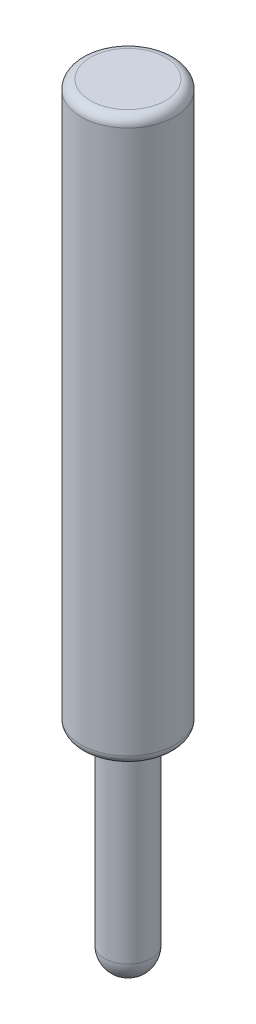
SolidWorks part; units mm, degrees
ref_plane "Front Plane" through (0, 0, 0) normal (0, 0, 1) x (1, 0, 0)
ref_plane "Top Plane" through (0, 0, 0) normal (0, 1, 0) x (1, 0, 0)
ref_plane "Right Plane" through (0, 0, 0) normal (1, 0, 0) x (0, 0, -1)
sketch "草图1" plane through (0, 0, 0) normal (0, 1, 0) x (1, 0, 0)
  circle A0 centre (0, 0) radius 5
  dimension "D1" = 10
extrude "凸台-拉伸1" add sketch "草图1" along normal blind 60
sketch "草图2" plane through (0, 0, 0) normal (0, 1, 0) x (1, 0, 0)
  circle A0 centre (0, 0) radius 2.5
  dimension "D1" = 5
extrude "凸台-拉伸2" add sketch "草图2" against normal blind 20
sketch "草图3" plane through (0, 0, 0) normal (0, 0, 1) x (1, 0, 0)
  line L0 (-2.5, -20) -> (2.5, -20) construction
  line L1 (0, -17.5) -> (0, -22.5)
  circle A0 centre (0, -20) radius 2.5
revolve "旋转1" add sketch "草图3" angle 360 about L1
fillet "圆角1" radius 1 2 edges at (0, 60, 5) (0, 0, 5)
sketch "草图4" plane through (0, 0, 0) normal (0, 0, 1) x (1, 0, 0)
  arc A0 (-2.5, -20) -> (2.5, -20) centre (0, -20) ccw construction
  point P0 (0, -22.5)
